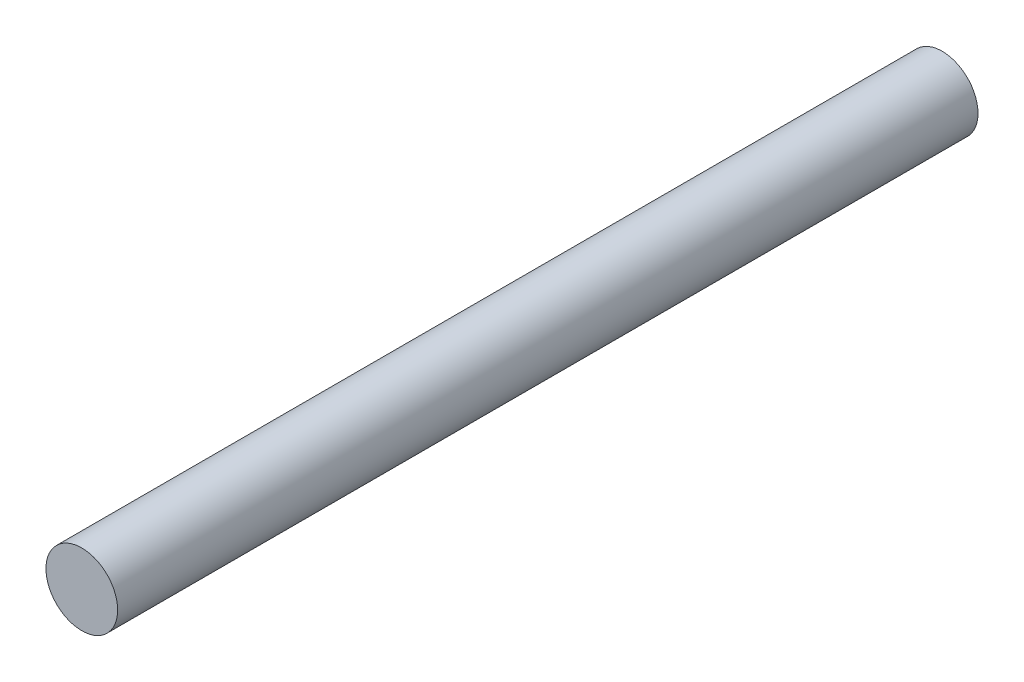
SolidWorks part; units mm, degrees
ref_plane "Спереди" through (0, 0, 0) normal (0, 0, 1) x (1, 0, 0)
ref_plane "Сверху" through (0, 0, 0) normal (0, 1, 0) x (1, 0, 0)
ref_plane "Справа" through (0, 0, 0) normal (1, 0, 0) x (0, 0, -1)
sketch "Эскиз1" plane through (0, 0, 0) normal (0, 0, 1) x (1, 0, 0)
  circle A0 centre (0, 0) radius 2.5
  dimension "D1" = 5
extrude "Бобышка-Вытянуть1" add sketch "Эскиз1" along normal blind 60
